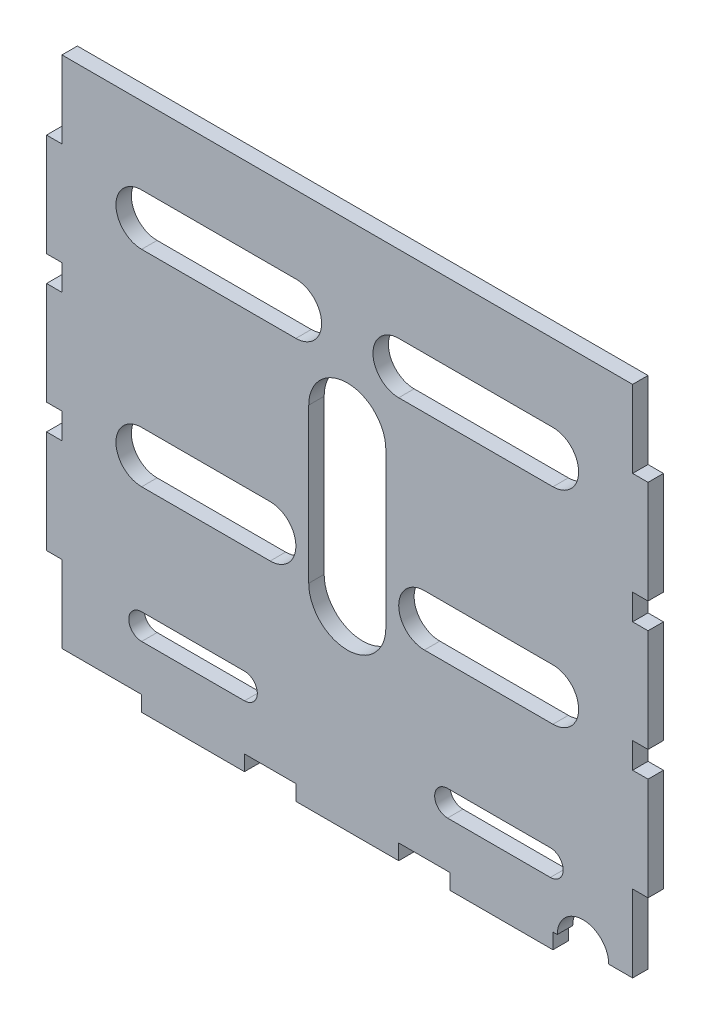
SolidWorks part; units mm, degrees
ref_plane "Front Plane" through (0, 0, 0) normal (0, 0, 1) x (1, 0, 0)
ref_plane "Top Plane" through (0, 0, 0) normal (0, 1, 0) x (1, 0, 0)
ref_plane "Right Plane" through (0, 0, 0) normal (1, 0, 0) x (0, 0, -1)
sketch "Sketch1" plane through (0, 0, 0) normal (0, 0, 1) x (1, 0, 0)
  line L0 (-55.5, 50) -> (-55.5, 35) construction
  line L1 (-55.5, -50) -> (-40, -50)
  line L2 (-55.5, -50) -> (-55.5, -35)
  line L3 (-55.5, 50) -> (55.5, 50)
  line L4 (55.5, -50) -> (55.5, -35)
  line L5 (-55.5, -50) -> (55.5, 50) construction
  line L6 (-55.5, 50) -> (55.5, -50) construction
  line L7 (-55.5, 15) -> (-55.5, 10) construction
  line L8 (-55.5, -10) -> (-55.5, -15) construction
  line L9 (-55.5, -35) -> (-55.5, -50) construction
  line L10 (-55.5, 35) -> (-55.5, 50)
  line L11 (-58.5, 35) -> (-55.5, 35)
  line L12 (-58.5, 35) -> (-58.5, 15)
  line L13 (-58.5, 15) -> (-55.5, 15)
  line L15 (55.5, 50) -> (55.5, 35) construction
  line L16 (-55.5, 10) -> (-55.5, 15)
  line L17 (-58.5, 10) -> (-55.5, 10)
  line L18 (-58.5, 10) -> (-58.5, -10)
  line L19 (-58.5, -10) -> (-55.5, -10)
  line L21 (55.5, 15) -> (55.5, 10) construction
  line L22 (55.5, -10) -> (55.5, -15) construction
  line L23 (-55.5, -15) -> (-58.5, -15)
  line L25 (-55.5, -35) -> (-58.5, -35)
  line L26 (-58.5, -15) -> (-58.5, -35)
  line L27 (55.5, 35) -> (55.5, 50)
  line L28 (55.5, 10) -> (55.5, 15)
  line L29 (-55.5, -15) -> (-55.5, -10)
  line L30 (55.5, -35) -> (55.5, -50) construction
  line L31 (55.5, -15) -> (55.5, -10)
  line L32 (55.5, 35) -> (58.5, 35)
  line L34 (55.5, 15) -> (58.5, 15)
  line L35 (58.5, 35) -> (58.5, 15)
  line L36 (-20, -50) -> (-10, -50)
  line L37 (10, -50) -> (20, -50)
  line L38 (55.5, 10) -> (58.5, 10)
  line L40 (55.5, -10) -> (58.5, -10)
  line L41 (58.5, 10) -> (58.5, -10)
  line L42 (-20, -50) -> (-10, -50) construction
  line L43 (10, -50) -> (20, -50) construction
  line L44 (55.5, -15) -> (58.5, -15)
  line L46 (55.5, -35) -> (58.5, -35)
  line L47 (58.5, -15) -> (58.5, -35)
  line L48 (40, -50) -> (40.8511, -50) construction
  line L49 (40, -50) -> (40.8511, -50)
  line L50 (-40, -53) -> (-20, -53)
  line L51 (-40, -53) -> (-40, -50)
  line L53 (-20, -53) -> (-20, -50)
  line L54 (50.8511, -50) -> (60, -50) construction
  line L55 (50.8511, -50) -> (55.5, -50)
  line L57 (-10, -50) -> (-10, -53)
  line L58 (-10, -53) -> (10, -53)
  line L59 (10, -50) -> (10, -53)
  line L60 (-40, 30) -> (-10, 30) construction
  line L61 (10, 30) -> (40, 30) construction
  line L63 (20, -50) -> (20, -53)
  line L64 (20, -53) -> (40, -53)
  line L65 (40, -50) -> (40, -53)
  line L66 (-40, 35) -> (-10, 35)
  line L67 (-40, 25) -> (-10, 25)
  line L68 (0, -15) -> (0, 15) construction
  line L69 (10, 35) -> (40, 35)
  line L70 (10, 25) -> (40, 25)
  line L71 (-40, -10) -> (-15, -10) construction
  line L72 (-7.5, -15) -> (-7.5, 15)
  line L73 (7.5, -15) -> (7.5, 15)
  line L74 (15, -10) -> (40, -10) construction
  line L75 (-40, -5) -> (-15, -5)
  line L76 (-40, -15) -> (-15, -15)
  line L77 (-40, -38.5568) -> (-20, -38.5568) construction
  line L78 (15, -5) -> (40, -5)
  line L79 (15, -15) -> (40, -15)
  line L80 (39.4968, -38.5568) -> (19.4968, -38.5568) construction
  line L81 (-40, -36.0568) -> (-20, -36.0568)
  line L82 (-40, -41.0568) -> (-20, -41.0568)
  line L84 (39.4968, -41.0568) -> (19.4968, -41.0568)
  line L85 (39.4968, -36.0568) -> (19.4968, -36.0568)
  arc A0 (50.8511, -50) -> (40.8511, -50) centre (45.8511, -50) ccw
  arc A1 (-40, 35) -> (-40, 25) centre (-40, 30) ccw
  arc A2 (-10, 25) -> (-10, 35) centre (-10, 30) ccw
  arc A3 (10, 35) -> (10, 25) centre (10, 30) ccw
  arc A4 (40, 25) -> (40, 35) centre (40, 30) ccw
  arc A5 (-7.5, -15) -> (7.5, -15) centre (0, -15) ccw
  arc A6 (7.5, 15) -> (-7.5, 15) centre (0, 15) ccw
  arc A7 (-40, -5) -> (-40, -15) centre (-40, -10) ccw
  arc A8 (-15, -15) -> (-15, -5) centre (-15, -10) ccw
  arc A9 (15, -5) -> (15, -15) centre (15, -10) ccw
  arc A10 (40, -15) -> (40, -5) centre (40, -10) ccw
  arc A11 (-40, -36.0568) -> (-40, -41.0568) centre (-40, -38.5568) ccw
  arc A12 (-20, -41.0568) -> (-20, -36.0568) centre (-20, -38.5568) ccw
  arc A13 (39.4968, -41.0568) -> (39.4968, -36.0568) centre (39.4968, -38.5568) ccw
  arc A14 (19.4968, -36.0568) -> (19.4968, -41.0568) centre (19.4968, -38.5568) ccw
  point P0 (0, 0)
  point P27 (0, -50)
  point P51 (-25, 30)
  point P58 (25, 30)
  point P65 (0, 0)
  point P72 (-27.5, -10)
  point P79 (27.5, -10)
  point P86 (-30, -38.5568)
  point P93 (29.4968, -38.5568)
  dimension "D21" = 20
  dimension "D1" = 111
  dimension "D2" = 100
  dimension "D3" = 20
  dimension "D4" = 20
  dimension "D5" = 20
  dimension "D6" = 3
  dimension "D7" = 3
  dimension "D8" = 3
  dimension "D9" = 20
  dimension "D10" = 20
  dimension "D11" = 20
  dimension "D12" = 3
  dimension "D13" = 3
  dimension "D14" = 3
  dimension "D15" = 20
  dimension "D16" = 20
  dimension "D17" = 20
  dimension "D18" = 3
  dimension "D19" = 3
  dimension "D20" = 3
  dimension "D22" = 40
  dimension "D23" = 15.5
  dimension "D24" = 25
extrude "Boss-Extrude1" add sketch "Sketch1" along normal blind 3
